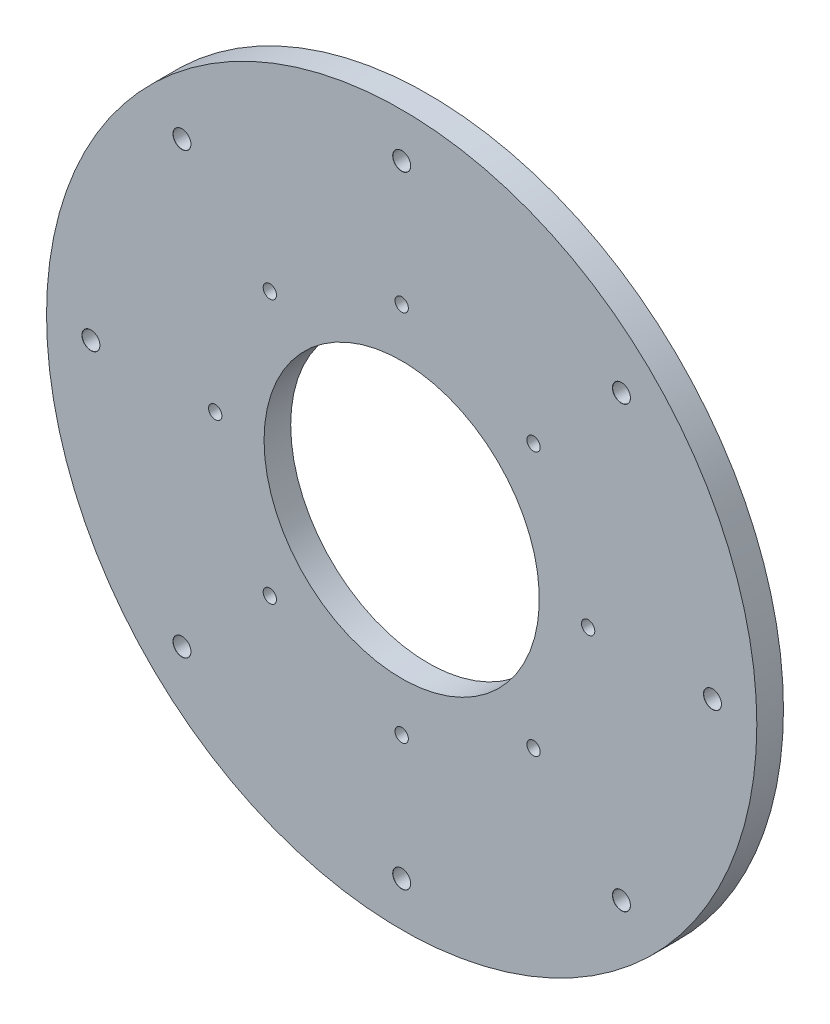
SolidWorks part; units mm, degrees
ref_plane "Front Plane" through (0, 0, 0) normal (0, 0, 1) x (1, 0, 0)
ref_plane "Top Plane" through (0, 0, 0) normal (0, 1, 0) x (1, 0, 0)
ref_plane "Right Plane" through (0, 0, 0) normal (1, 0, 0) x (0, 0, -1)
sketch "Sketch2" plane through (0, 0, 0) normal (0, 0, 1) x (1, 0, 0)
  line L0 (0, 0) -> (0, 90.7247) construction
  circle A0 centre (0, 0) radius 80
  circle A1 centre (0, 0) radius 31
  point P0 (0, 0)
  point P4 (0, 70)
  point P5 (49.4975, 49.4975)
  point P8 (70, 0)
  point P9 (49.4975, -49.4975)
  point P10 (0, -70)
  point P11 (-49.4975, -49.4975)
  point P12 (-70, 0)
  point P13 (-49.4975, 49.4975)
  point P14 (0, 0)
  dimension "D3" = 160
  dimension "D4" = 62
  dimension "D1" = 70
  dimension "D2" = 8
extrude "Boss-Extrude1" add sketch "Sketch2" along normal blind 6
sketch "Sketch9" plane through (0, 0, 0) normal (0, 0, 1) x (1, 0, 0)
  line L0 (0, 0) -> (0, 90.7247) construction
  circle A0 centre (0, 0) radius 80
  circle A1 centre (0, 0) radius 31
  point P0 (0, 0)
  point P4 (0, 70)
  point P5 (49.4975, 49.4975)
  point P8 (70, 0)
  point P9 (49.4975, -49.4975)
  point P10 (0, -70)
  point P11 (-49.4975, -49.4975)
  point P12 (-70, 0)
  point P13 (-49.4975, 49.4975)
  point P14 (0, 0)
  dimension "D3" = 160
  dimension "D4" = 62
  dimension "D1" = 70
  dimension "D2" = 8
hole_wizard "Ø4.0mm Dowel Hole1" positions "Sketch10" profile "Sketch11" hole size "Ø4.0" standard "ISO"
sketch "Sketch10" plane through (0, 0, 6) normal (0, 0, 1) x (1, 0, 0)
  point P0 (0, 70)
  point P3 (-49.4975, 49.4975)
  point P6 (-70, 0)
  point P9 (-49.4975, -49.4975)
  point P12 (0, -70)
  point P15 (49.4975, -49.4975)
  point P18 (70, 0)
  point P21 (49.4975, 49.4975)
sketch "Sketch11" plane through (0, 70, 6) normal (1, 0, 0) x (0, -1, 0)
  line L0 (0, 0) -> (0, 7.2007)
  line L1 (0, 7.2007) -> (2, 5.999)
  line L2 (2, 5.999) -> (2, 0.025)
  line L3 (2, 0.025) -> (2.025, 0)
  line L5 (2.025, 0) -> (0, 0)
  line L6 (-2, 0.025) -> (-2.025, 0) construction
  line L10 (0, 7.2007) -> (-2, 5.999) construction
  line L11 (0, -6.35) -> (0, 107.95) construction
  dimension "Hole Dia." = 4
  dimension "Hole Depth" = 5.999
  dimension "Near C'Sink Dia." = 4.05
  dimension "Near C'Sink Angle" = 90
  dimension "Drill Angle" = 118
sketch "Sketch13" plane through (0, 0, 0) normal (0, 0, 1) x (1, 0, 0)
  line L0 (0, 0) -> (40.3784, 77.1924) construction
  line L1 (0, 0) -> (-24.0217, -45.9229) construction
  point P3 (-17.1497, -32.7855)
  point P4 (-35.3095, -11.0562)
  point P5 (0, 0)
  point P7 (-32.7855, 17.1497)
  point P8 (-11.0562, 35.3095)
  point P9 (17.1497, 32.7855)
  point P10 (35.3095, 11.0562)
  point P11 (32.7855, -17.1497)
  point P12 (11.0562, -35.3095)
  point P13 (0, 0)
  dimension "D1" = 37
  dimension "D2" = 8
hole_wizard "Ø3.0mm Dowel Hole1" positions "Sketch14" profile "Sketch15" hole size "Ø3.0" standard "ISO"
sketch "Sketch14" plane through (0, 0, 0) normal (0, 0, -1) x (-1, 0, 0)
  line L3 (0, 0) -> (-70, 0) construction
  circle A3 centre (0, 0) radius 42 construction
  point P52 (-42, 0)
  point P61 (-29.6985, 29.6985)
  point P62 (0, 42)
  point P63 (29.6985, 29.6985)
  point P64 (42, 0)
  point P65 (29.6985, -29.6985)
  point P66 (0, -42)
  point P67 (-29.6985, -29.6985)
  dimension "D1" = 84
  dimension "D2" = 8
sketch "Sketch15" plane through (29.6985, -29.6985, 0) normal (1, 0, 0) x (0, 1, 0)
  line L0 (0, 0) -> (0, 6.9013)
  line L1 (0, 6.9013) -> (1.5, 6)
  line L2 (1.5, 6) -> (1.5, 0.025)
  line L3 (1.5, 0.025) -> (1.525, 0)
  line L5 (1.525, 0) -> (0, 0)
  line L6 (-1.5, 0.025) -> (-1.525, 0) construction
  line L10 (0, 6.9013) -> (-1.5, 6) construction
  line L11 (0, -6.35) -> (0, 107.95) construction
  dimension "Hole Dia." = 3
  dimension "Hole Depth" = 6
  dimension "Near C'Sink Dia." = 3.05
  dimension "Near C'Sink Angle" = 90
  dimension "Drill Angle" = 118
